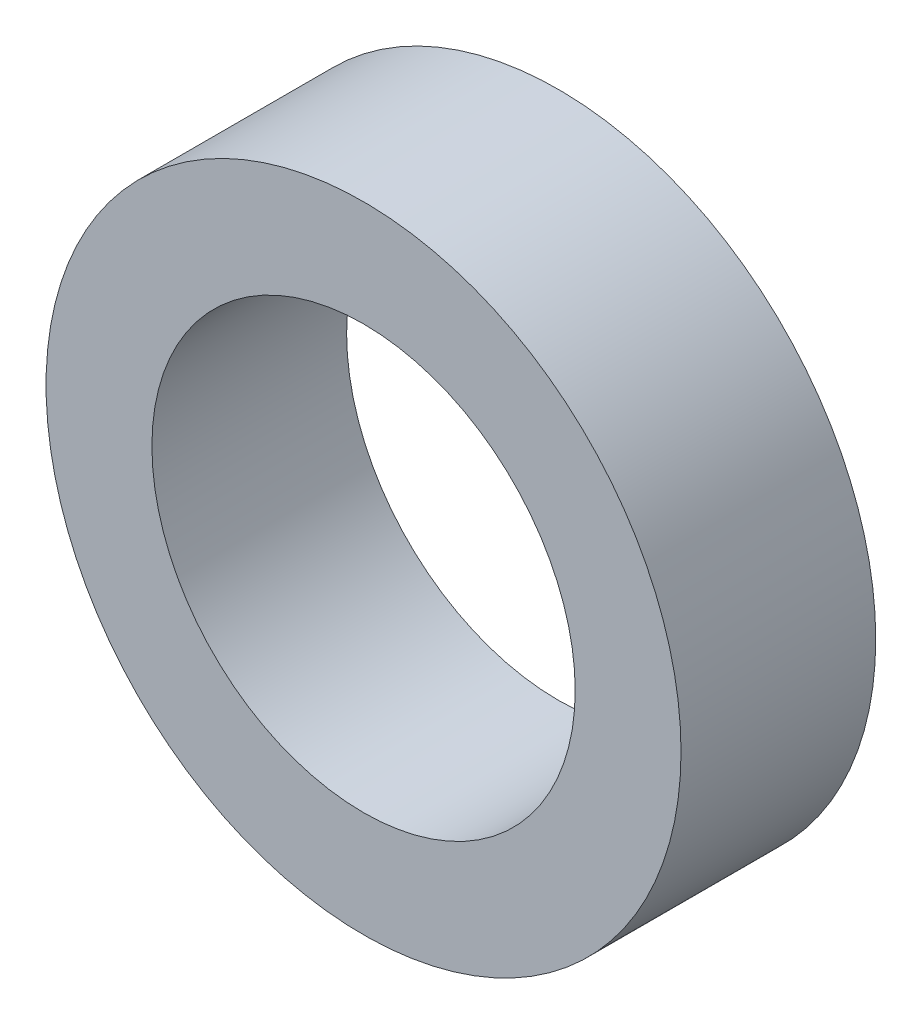
SolidWorks part; units mm, degrees
ref_plane "Front Plane" through (0, 0, 0) normal (0, 0, 1) x (1, 0, 0)
ref_plane "Top Plane" through (0, 0, 0) normal (0, 1, 0) x (1, 0, 0)
ref_plane "Right Plane" through (0, 0, 0) normal (1, 0, 0) x (0, 0, -1)
sketch "Sketch1" plane through (0, 0, 0) normal (0, 0, 1) x (1, 0, 0)
  circle A0 centre (0, 0) radius 25
  circle A1 centre (0, 0) radius 37.5
  dimension "D1" = 75
  dimension "D2" = 50
extrude "Boss-Extrude1" add sketch "Sketch1" along normal blind 23
